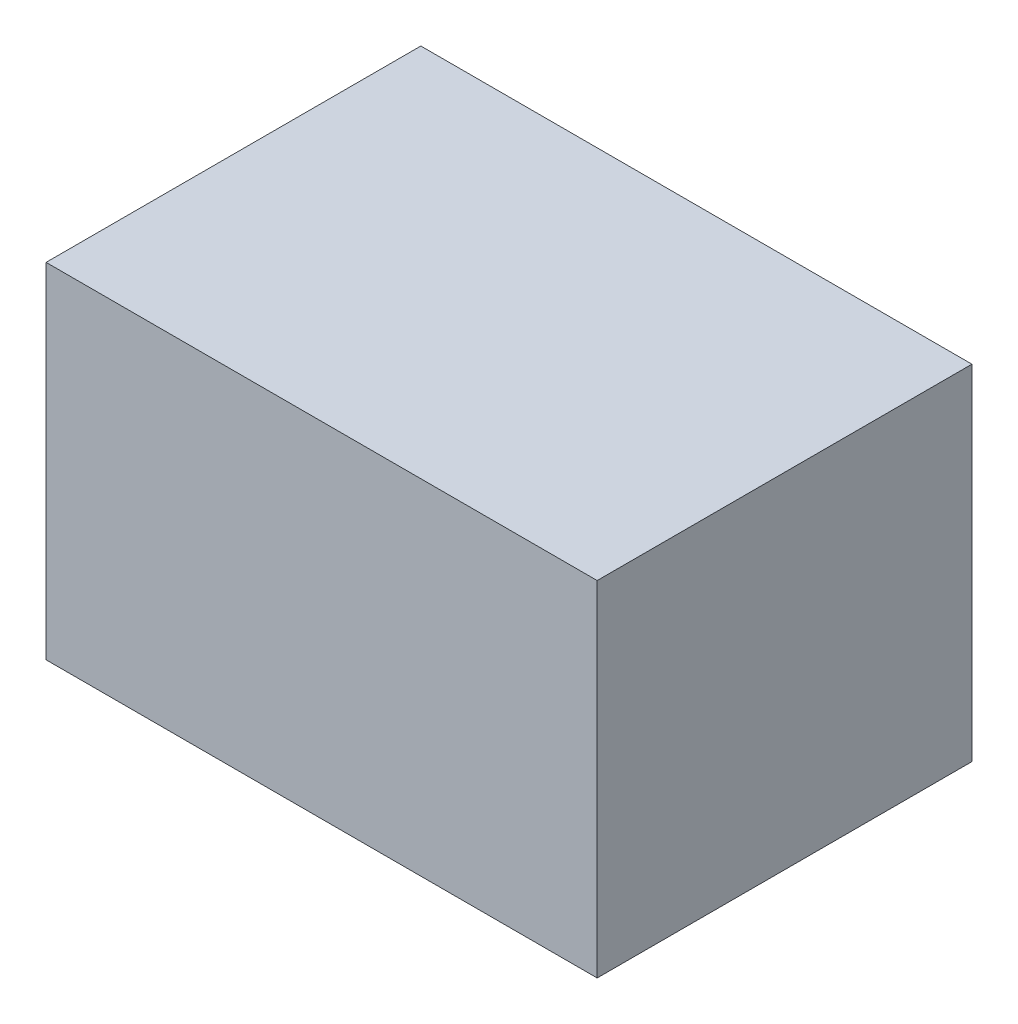
SolidWorks part; units mm, degrees
ref_plane "Front Plane" through (0, 0, 0) normal (0, 0, 1) x (1, 0, 0)
ref_plane "Top Plane" through (0, 0, 0) normal (0, 1, 0) x (1, 0, 0)
ref_plane "Right Plane" through (0, 0, 0) normal (1, 0, 0) x (0, 0, -1)
sketch "Sketch1" plane through (0, 0, 0) normal (0, 0, 1) x (1, 0, 0)
  line L1 (0, 0) -> (825.5, 0)
  line L2 (0, 0) -> (0, 515.62)
  line L3 (0, 515.62) -> (825.5, 515.62)
  line L4 (825.5, 0) -> (825.5, 515.62)
  dimension "D1" = 515.62
  dimension "D2" = 825.5
extrude "Boss-Extrude1" add sketch "Sketch1" along normal blind 561.34
sketch "Sketch2" plane through (0, 0, 0) normal (0, 0, -1) x (-1, 0, 0)
  line L0 (-825.5, 0) -> (-825.5, 515.62) construction
  line L1 (-812.8, 12.7) -> (-12.7, 12.7)
  line L2 (-812.8, 12.7) -> (-812.8, 502.92)
  line L3 (-812.8, 502.92) -> (-12.7, 502.92)
  line L4 (-12.7, 12.7) -> (-12.7, 502.92)
  line L5 (0, 0) -> (-825.5, 0) construction
  dimension "D1" = 490.22
  dimension "D2" = 800.1
  dimension "D3" = 12.7
  dimension "D4" = 12.7
extrude "Cut-Extrude1" cut sketch "Sketch2" against normal blind 535.94
